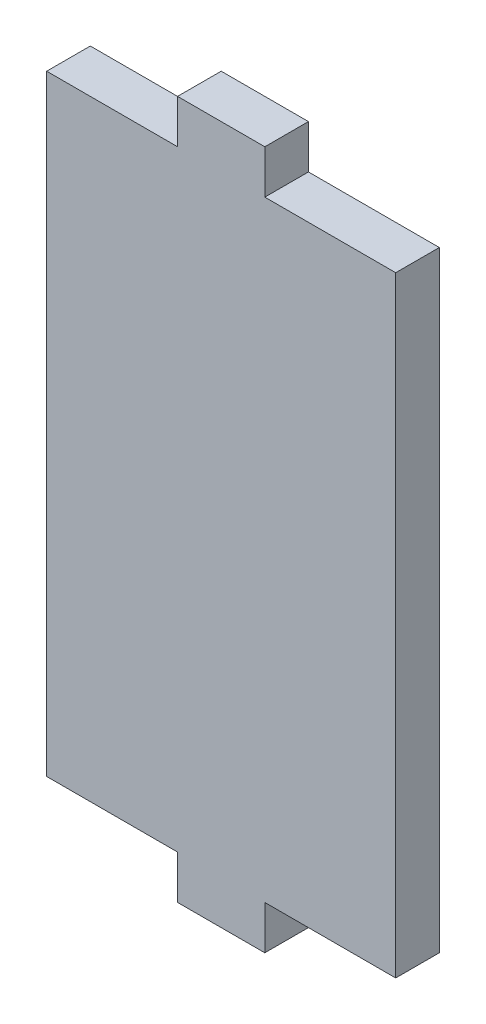
SolidWorks part; units mm, degrees
ref_plane "Front Plane" through (0, 0, 0) normal (0, 0, 1) x (1, 0, 0)
ref_plane "Top Plane" through (0, 0, 0) normal (0, 1, 0) x (1, 0, 0)
ref_plane "Right Plane" through (0, 0, 0) normal (1, 0, 0) x (0, 0, -1)
sketch "Sketch1" plane through (0, 0, 0) normal (0, 0, 1) x (1, 0, 0)
  line L0 (-3.175, 0) -> (3.175, 0)
  line L1 (3.175, 0) -> (3.175, 3.175)
  line L2 (3.175, 3.175) -> (12.7, 3.175)
  line L3 (12.7, 3.175) -> (12.7, 47.625)
  line L4 (12.7, 47.625) -> (3.175, 47.625)
  line L5 (3.175, 47.625) -> (3.175, 50.8)
  line L6 (3.175, 50.8) -> (-3.175, 50.8)
  line L7 (-3.175, 50.8) -> (-3.175, 47.625)
  line L8 (-3.175, 47.625) -> (-12.7, 47.625)
  line L9 (-12.7, 47.625) -> (-12.7, 3.175)
  line L10 (-12.7, 3.175) -> (-3.175, 3.175)
  line L11 (-3.175, 3.175) -> (-3.175, 0)
  point P4 (0, 0)
  dimension "D1" = 6.35
  dimension "D2" = 3.175
  dimension "D3" = 25.4
  dimension "D4" = 50.8
extrude "Boss-Extrude1" add sketch "Sketch1" along normal blind 3.175
